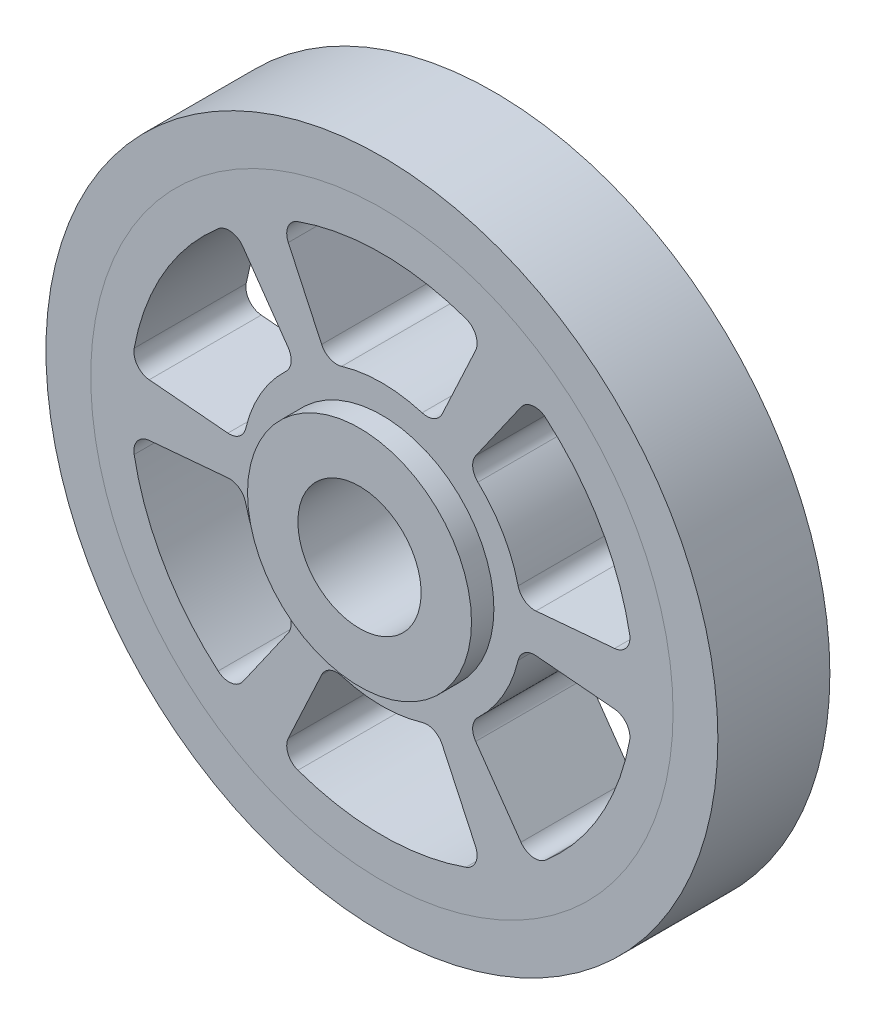
SolidWorks part; units mm, degrees
ref_plane "Front Plane" through (0, 0, 0) normal (0, 0, 1) x (1, 0, 0)
ref_plane "Top Plane" through (0, 0, 0) normal (0, 1, 0) x (1, 0, 0)
ref_plane "Right Plane" through (0, 0, 0) normal (1, 0, 0) x (0, 0, -1)
sketch "Sketch1" plane through (0, 0, 0) normal (0, 0, 1) x (1, 0, 0)
  circle A0 centre (0, 0) radius 76.2
  circle A1 centre (0, 0) radius 66.04
  dimension "D1" = 152.4
  dimension "D2" = 10.16
extrude "Boss-Extrude1" add sketch "Sketch1" along normal blind 25.4
sketch "Sketch2" plane through (0, 0, 0) normal (0, 0, 1) x (1, 0, 0)
  line L0 (0, 25.4) -> (0, 66.04) construction
  line L1 (13.666, 32.4517) -> (21.233, 48.6793)
  line L2 (34.937, 4.3907) -> (52.774, 5.9513)
  line L3 (-13.666, 32.4517) -> (-21.233, 48.6793)
  line L4 (21.271, 28.0609) -> (31.541, 42.728)
  line L5 (21.271, -28.0609) -> (31.541, -42.728)
  line L6 (34.937, -4.3907) -> (52.774, -5.9513)
  line L7 (-13.666, -32.4517) -> (-21.233, -48.6793)
  line L8 (13.666, -32.4517) -> (21.233, -48.6793)
  line L9 (-34.937, -4.3907) -> (-52.774, -5.9513)
  line L10 (-21.271, -28.0609) -> (-31.541, -42.728)
  line L11 (-21.271, 28.0609) -> (-31.541, 42.728)
  line L12 (-34.937, 4.3907) -> (-52.774, 5.9513)
  circle A0 centre (0, 0) radius 66.04
  circle A1 centre (0, 0) radius 25.4
  arc A2 (19.05, 53.8815) -> (-19.05, 53.8815) centre (0, 0) ccw
  arc A3 (9.1187, 30.4124) -> (-9.1187, 30.4124) centre (0, 0) ccw
  arc A4 (-9.1187, 30.4124) -> (-13.666, 32.4517) centre (-10.213, 34.0618) cw
  arc A5 (9.1187, 30.4124) -> (13.666, 32.4517) centre (10.213, 34.0618) ccw
  arc A6 (19.05, 53.8815) -> (21.233, 48.6793) centre (17.78, 50.2894) cw
  arc A7 (-19.05, 53.8815) -> (-21.233, 48.6793) centre (-17.78, 50.2894) ccw
  arc A8 (56.1878, 10.443) -> (37.1378, 43.4386) centre (0, 0) ccw
  arc A9 (30.8972, 7.3091) -> (21.7785, 23.1032) centre (0, 0) ccw
  arc A10 (21.7785, 23.1032) -> (21.271, 28.0609) centre (24.3919, 25.8756) cw
  arc A11 (30.8972, 7.3091) -> (34.937, 4.3907) centre (34.6049, 8.1862) ccw
  arc A12 (56.1878, 10.443) -> (52.774, 5.9513) centre (52.4419, 9.7468) cw
  arc A13 (37.1378, 43.4386) -> (31.541, 42.728) centre (34.6619, 40.5426) ccw
  arc A14 (37.1378, -43.4386) -> (56.1878, -10.443) centre (0, 0) ccw
  arc A15 (21.7785, -23.1032) -> (30.8972, -7.3091) centre (0, 0) ccw
  arc A16 (30.8972, -7.3091) -> (34.937, -4.3907) centre (34.6049, -8.1862) cw
  arc A17 (21.7785, -23.1032) -> (21.271, -28.0609) centre (24.3919, -25.8756) ccw
  arc A18 (37.1378, -43.4386) -> (31.541, -42.728) centre (34.6619, -40.5426) cw
  arc A19 (56.1878, -10.443) -> (52.774, -5.9513) centre (52.4419, -9.7468) ccw
  arc A20 (-19.05, -53.8815) -> (19.05, -53.8815) centre (0, 0) ccw
  arc A21 (-9.1187, -30.4124) -> (9.1187, -30.4124) centre (0, 0) ccw
  arc A22 (9.1187, -30.4124) -> (13.666, -32.4517) centre (10.213, -34.0618) cw
  arc A23 (-9.1187, -30.4124) -> (-13.666, -32.4517) centre (-10.213, -34.0618) ccw
  arc A24 (-19.05, -53.8815) -> (-21.233, -48.6793) centre (-17.78, -50.2894) cw
  arc A25 (19.05, -53.8815) -> (21.233, -48.6793) centre (17.78, -50.2894) ccw
  arc A26 (-56.1878, -10.443) -> (-37.1378, -43.4386) centre (0, 0) ccw
  arc A27 (-30.8972, -7.3091) -> (-21.7785, -23.1032) centre (0, 0) ccw
  arc A28 (-21.7785, -23.1032) -> (-21.271, -28.0609) centre (-24.3919, -25.8756) cw
  arc A29 (-30.8972, -7.3091) -> (-34.937, -4.3907) centre (-34.6049, -8.1862) ccw
  arc A30 (-56.1878, -10.443) -> (-52.774, -5.9513) centre (-52.4419, -9.7468) cw
  arc A31 (-37.1378, -43.4386) -> (-31.541, -42.728) centre (-34.6619, -40.5426) ccw
  arc A32 (-37.1378, 43.4386) -> (-56.1878, 10.443) centre (0, 0) ccw
  arc A33 (-21.7785, 23.1032) -> (-30.8972, 7.3091) centre (0, 0) ccw
  arc A34 (-30.8972, 7.3091) -> (-34.937, 4.3907) centre (-34.6049, 8.1862) cw
  arc A35 (-21.7785, 23.1032) -> (-21.271, 28.0609) centre (-24.3919, 25.8756) ccw
  arc A36 (-37.1378, 43.4386) -> (-31.541, 42.728) centre (-34.6619, 40.5426) cw
  arc A37 (-56.1878, 10.443) -> (-52.774, 5.9513) centre (-52.4419, 9.7468) ccw
  point P18 (0, 57.15)
  point P80 (0, 0)
  dimension "D1" = 50.8
  dimension "D4" = 114.3
  dimension "D5" = 63.5
  dimension "D6" = 3.81
  dimension "D8" = 38.1
  dimension "D2" = 25
  dimension "D3" = 25
  dimension "D7" = 6
extrude "Boss-Extrude2" add sketch "Sketch2" along normal blind 25.4 separate body
ref_plane "Mid_Plane" through (0, 0, 12.7) normal (0, 0, -1) x (-1, 0, 0)
sketch "Sketch3" plane through (0, 0, 12.7) normal (0, 0, -1) x (-1, 0, 0)
  circle A0 centre (0, 0) radius 25.4 construction
  circle A1 centre (0, 0) radius 25.4
  circle A2 centre (0, 0) radius 13.97
  dimension "D1" = 27.94
extrude "Boss-Extrude3" add sketch "Sketch3" along normal blind 17.78 and the other way blind 17.78
